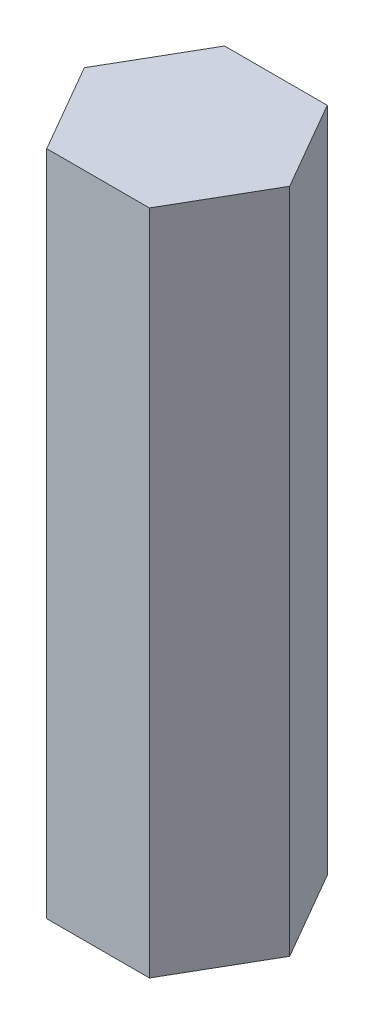
SolidWorks part; units mm, degrees
ref_plane "Front Plane" through (0, 0, 0) normal (0, 0, 1) x (1, 0, 0)
ref_plane "Top Plane" through (0, 0, 0) normal (0, 1, 0) x (1, 0, 0)
ref_plane "Right Plane" through (0, 0, 0) normal (1, 0, 0) x (0, 0, -1)
sketch "Sketch1" plane through (0, 0, 0) normal (0, 1, 0) x (1, 0, 0)
  line L1 (2.3094, 0) -> (1.1547, 2)
  line L2 (1.1547, 2) -> (-1.1547, 2)
  line L3 (-1.1547, 2) -> (-2.3094, 0)
  line L4 (-2.3094, 0) -> (-1.1547, -2)
  line L5 (-1.1547, -2) -> (1.1547, -2)
  line L6 (1.1547, -2) -> (2.3094, 0)
  circle A0 centre (0, 0) radius 2 construction
  dimension "D1" = 4
extrude "Boss-Extrude1" add sketch "Sketch1" along normal blind 15
